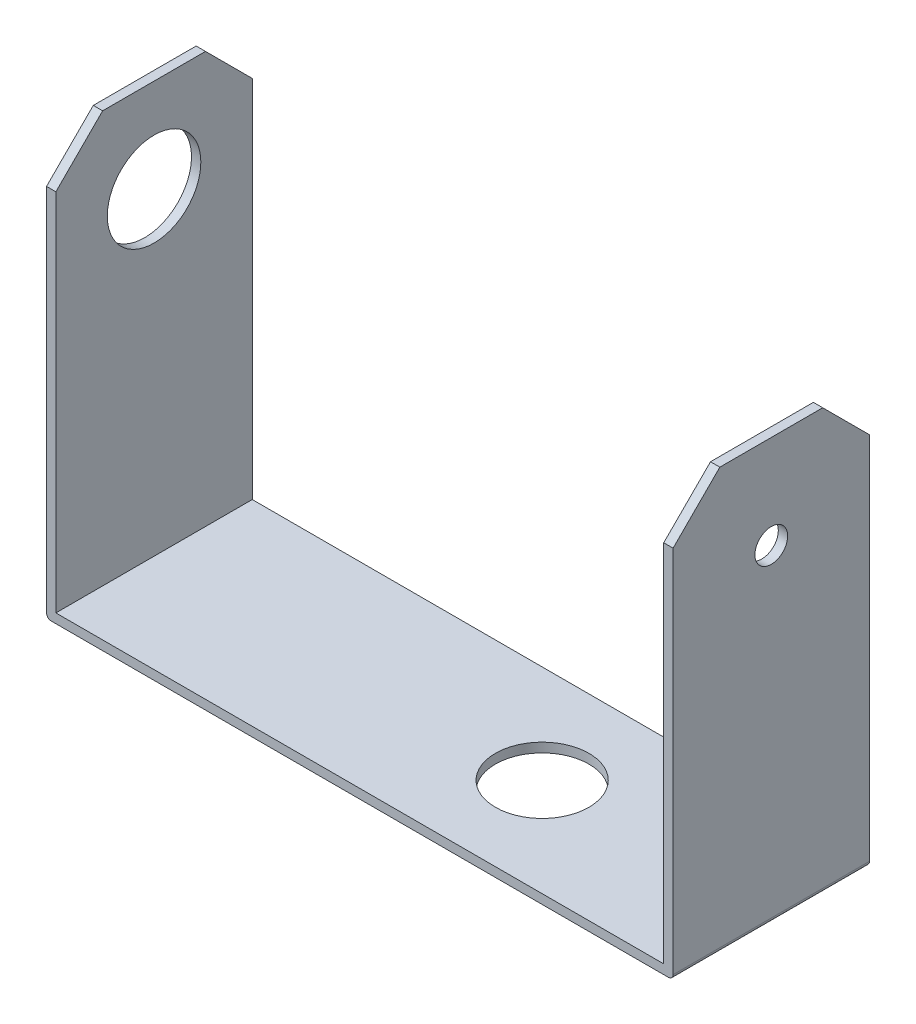
SolidWorks part; units mm, degrees
ref_plane "前视基准面" through (0, 0, 0) normal (0, 0, 1) x (1, 0, 0)
ref_plane "上视基准面" through (0, 0, 0) normal (0, 1, 0) x (1, 0, 0)
ref_plane "右视基准面" through (0, 0, 0) normal (1, 0, 0) x (0, 0, -1)
sketch "草图1" plane through (0, 0, 0) normal (0, 1, 0) x (1, 0, 0)
  line L0 (0, 0) -> (-67, 0)
  line L1 (-67, 0) -> (-67, 21)
  line L2 (-67, 21) -> (0, 21)
  line L3 (0, 21) -> (0, 0)
  dimension "D1" = 67
  dimension "D2" = 21
extrude "凸台-拉伸1" add sketch "草图1" along normal blind 45
shell "抽壳1" thickness 1
fillet "圆角1" radius 0.5 2 edges at (0, 0, -10.5) (-67, 0, -10.5)
chamfer "倒角1" distance 5 distance2 5 4 edges at (-66.5, 45, -21) (-66.5, 45, 0) (-0.5, 45, -21) (-0.5, 45, 0)
hole_wizard "Ø10.0 (10) 直径槽口1" positions "草图2" profile "草图3" size "Ø10.0" standard "GB"
sketch "草图2" plane through (-67, 0, 0) normal (-1, 0, 0) x (0, 0, 1)
  line L0 (-16, 45) -> (-5, 45) construction
  line L2 (0, 40) -> (0, 0.5) construction
  point P0 (-10.5, 35)
  dimension "D1" = 10
  dimension "D2" = 10.5
sketch "草图3" plane through (-67, 35, -10.5) normal (0, 1, 0) x (0, 0, 1)
  line L0 (0, 0) -> (0, 1)
  line L1 (0, 1) -> (5, 1)
  line L2 (5, 1) -> (5, 0)
  line L5 (5, 0) -> (0, 0)
  line L11 (0, -6.35) -> (0, 107.95) construction
  dimension "通孔孔直径" = 10
  dimension "通孔孔深度" = 1
hole_wizard "Ø10.0 (10) 直径槽口2" positions "草图4" profile "草图5" size "Ø10.0" standard "GB" slot yes end condition up to next
sketch "草图4" plane through (0, 1, 0) normal (0, 1, 0) x (1, 0, 0)
  line L0 (-1, 0) -> (-1, 21) construction
  line L1 (-66, 0) -> (-1, 0) construction
  point P0 (-24.5, 10.5)
  dimension "D1" = 23.5
  dimension "D2" = 10.5
sketch "草图5" plane through (-24.5, 1, -10.5) normal (1, 0, 0) x (0, 0, 1)
  line L0 (0, 0) -> (0, 1)
  line L1 (0, 1) -> (5, 1)
  line L2 (5, 1) -> (5, 0)
  line L5 (5, 0) -> (0, 0)
  line L11 (0, -6.35) -> (0, 107.95) construction
  dimension "通孔孔直径" = 10
  dimension "通孔孔深度" = 1
hole_wizard "Ø3.5 (3.5) 直径槽口1" positions "草图6" profile "草图7" size "Ø3.5" standard "GB" slot yes end condition up to next
sketch "草图6" plane through (0, 0, 0) normal (1, 0, 0) x (0, 0, -1)
  line L0 (5, 45) -> (16, 45) construction
  line L1 (0, 40) -> (0, 0.5) construction
  point P0 (10.5, 35)
  dimension "D1" = 10
  dimension "D2" = 10.5
sketch "草图7" plane through (0, 35, -10.5) normal (0, 1, 0) x (0, 0, -1)
  line L0 (0, 0) -> (0, 1)
  line L1 (0, 1) -> (1.75, 1)
  line L2 (1.75, 1) -> (1.75, 0)
  line L5 (1.75, 0) -> (0, 0)
  line L11 (0, -6.35) -> (0, 107.95) construction
  dimension "通孔孔直径" = 3.5
  dimension "通孔孔深度" = 1
